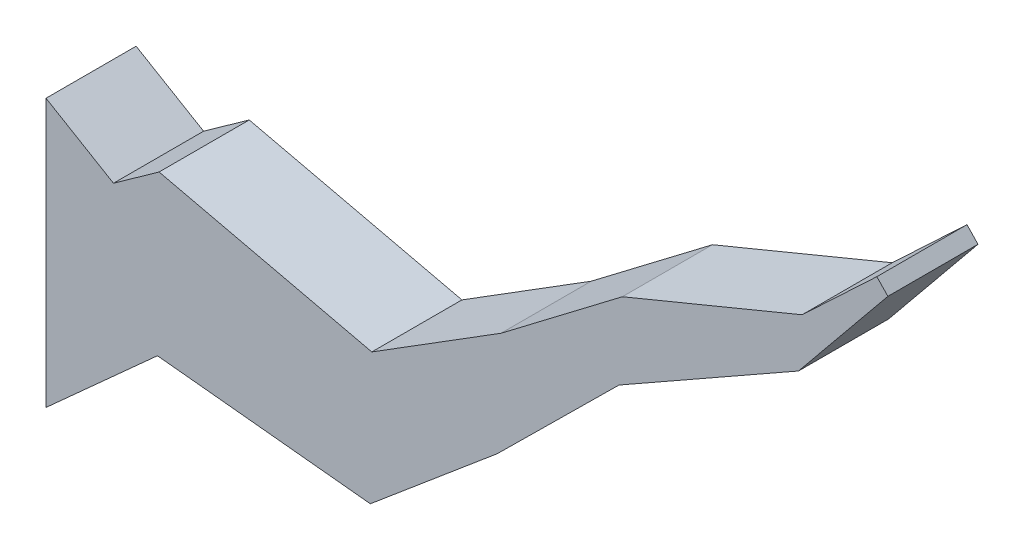
SolidWorks part; units mm, degrees
ref_plane "Ebene vorne" through (0, 0, 0) normal (0, 0, 1) x (1, 0, 0)
ref_plane "Ebene oben" through (0, 0, 0) normal (0, 1, 0) x (1, 0, 0)
ref_plane "Ebene rechts" through (0, 0, 0) normal (1, 0, 0) x (0, 0, -1)
sketch "Model" plane through (0, 0, 0) normal (0, 0, 1) x (1, 0, 0)
  line L15 (27.7572, 17.8239) -> (25.2694, 15.482)
  line L16 (25.2694, 15.482) -> (19.2854, 13.0089)
  line L17 (19.2854, 13.0089) -> (15.2467, 9.9376)
  line L18 (15.2467, 9.9376) -> (10.9451, 7.2481)
  line L19 (10.9451, 7.2481) -> (3.8649, 8.8954)
  line L20 (3.8649, 8.8954) -> (2.3461, 7.8117)
  line L21 (2.3461, 7.8117) -> (0.1, 9.1392)
  line L22 (0.1, 9.1392) -> (0.1, 0.2248)
  line L23 (0.1, 0.2248) -> (3.8096, 3.57)
  line L24 (3.8096, 3.57) -> (10.8953, 2.845)
  line L25 (10.8953, 2.845) -> (15.1224, 6.403)
  line L26 (15.1224, 6.403) -> (19.1743, 10.408)
  line L27 (19.1743, 10.408) -> (25.1486, 13.7997)
  line L28 (25.1486, 13.7997) -> (28.1241, 17.4407)
  line L29 (28.1241, 17.4407) -> (27.7572, 17.8239)
extrude "Aufsatz-Linear austragen1" add sketch "Model" along normal blind 3
